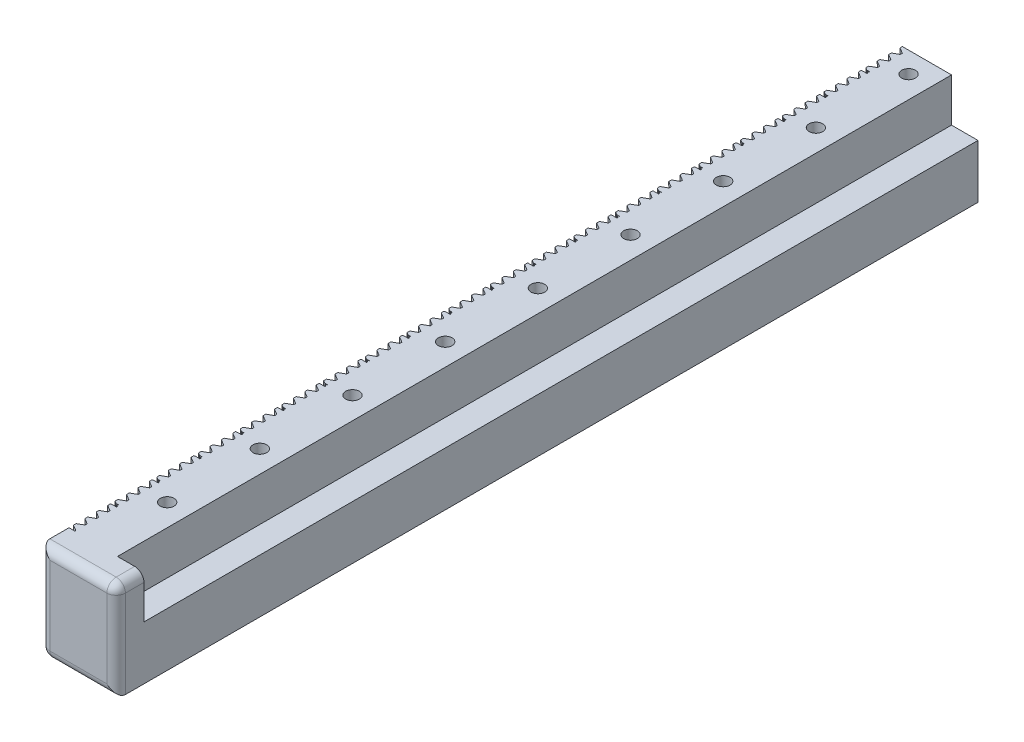
SolidWorks part; units mm, degrees
ref_plane "Front Plane" through (0, 0, 0) normal (0, 0, 1) x (1, 0, 0)
ref_plane "Top Plane" through (0, 0, 0) normal (0, 1, 0) x (1, 0, 0)
ref_plane "Right Plane" through (0, 0, 0) normal (1, 0, 0) x (0, 0, -1)
sketch "Sketch1" plane through (0, 0, 0) normal (0, 0, 1) x (1, 0, 0)
  line L0 (8.155, 3.5595) -> (8.155, -2.2289)
  line L1 (6.255, 0) -> (0.2882, 0)
  line L3 (0, 8.253) -> (5.3, 8.253)
  line L4 (5.3, 3.5595) -> (5.3, 8.253)
  line L5 (0.2882, 0) -> (0, 8.253)
  line L7 (5.3, 3.5595) -> (8.155, 3.5595)
  line L11 (8.155, -2.2289) -> (6.255, -2.2289)
  line L12 (6.255, 0) -> (6.255, -2.2289)
  dimension "D1" = 5.3
  dimension "D2" = 8.253
  dimension "D3" = 1.9
  dimension "D4" = 2.855
  dimension "D6" = 88
extrude "Boss-Extrude1" add sketch "Sketch1" along normal blind 90
sketch "Sketch2" plane through (0, 0, 90) normal (0, 0, 1) x (1, 0, 0)
  line L1 (0, 8.253) -> (8.155, 8.253)
  line L2 (0, 8.253) -> (0, -2.2289)
  line L3 (0, -2.2289) -> (8.155, -2.2289)
  line L4 (8.155, 8.253) -> (8.155, -2.2289)
extrude "Boss-Extrude2" add sketch "Sketch2" along normal blind 3
fillet "Fillet1" radius 1 6 edges at (4.0775, 8.253, 93) (8.155, 3.0121, 93) (4.0775, -2.2289, 93) (0, 3.0121, 93) (0, -2.2289, 91.5) (8.155, 8.253, 91.5)
sketch "Sketch3" plane through (5.3, 0, 0) normal (0, 1, 0) x (0, 0, -1)
  line L0 (-87.5812, 4.6774) -> (-88.0715, 5.5507)
  line L1 (-88.0715, 5.5507) -> (-88.5898, 4.6774)
  line L2 (-88.8112, 4.6774) -> (-89.3015, 5.5507)
  line L3 (-89.3015, 5.5507) -> (-89.8198, 4.6774)
  line L4 (-89.3983, 4.4813) -> (-88.7803, 4.4739) [skipped]
  line L5 (-86.3512, 4.6774) -> (-86.8415, 5.5507)
  line L6 (-86.8415, 5.5507) -> (-87.3598, 4.6774)
  line L7 (-85.1212, 4.6774) -> (-85.6115, 5.5507)
  line L8 (-85.6115, 5.5507) -> (-86.1298, 4.6774)
  line L149 (-89.9324, 4.6774) -> (-89.9324, 6.9221)
  line L150 (-89.9324, 6.9221) -> (-85.1212, 6.9221)
  line L154 (-89.8198, 4.6774) -> (-89.9324, 4.6774)
  line L155 (-88.5898, 4.6774) -> (-88.8112, 4.6774)
  line L156 (-87.3598, 4.6774) -> (-87.5812, 4.6774)
  line L157 (-86.1298, 4.6774) -> (-86.3512, 4.6774)
  line L158 (-85.1212, 6.9221) -> (-85.1212, 4.6774)
  line L160 (-83.1621, 7.6054) -> (-83.4775, 7.0739) [skipped]
  line L161 (-83.735, 6.5902) -> (-84.3402, 7.668) [skipped]
  line L162 (-81.9321, 7.6054) -> (-82.5629, 6.5424) [skipped]
  line L163 (-82.505, 6.5902) -> (-83.1102, 7.668) [skipped]
  line L164 (-80.7021, 7.6054) -> (-81.3329, 6.5424) [skipped]
  line L165 (-81.275, 6.5902) -> (-81.8802, 7.668) [skipped]
  line L166 (-79.4721, 7.6054) -> (-80.1029, 6.5424) [skipped]
  line L167 (-80.045, 6.5902) -> (-80.6502, 7.668) [skipped]
  line L168 (-78.2421, 7.6054) -> (-78.8729, 6.5424) [skipped]
  line L169 (-78.815, 6.5902) -> (-79.4202, 7.668) [skipped]
  line L170 (-77.0121, 7.6054) -> (-77.6429, 6.5424) [skipped]
  line L171 (-75.7821, 7.6054) -> (-76.4129, 6.5424) [skipped]
  line L172 (-84.965, 6.5902) -> (-85.5702, 7.668) [skipped]
  line L173 (-49.295, 6.5902) -> (-49.9002, 7.668) [skipped]
  line L174 (-47.4921, 7.6054) -> (-48.1229, 6.5424) [skipped]
  line L175 (-48.065, 6.5902) -> (-48.6702, 7.668) [skipped]
  line L176 (-46.2621, 7.6054) -> (-46.8929, 6.5424) [skipped]
  line L177 (-46.835, 6.5902) -> (-47.4402, 7.668) [skipped]
  line L178 (-45.0321, 7.6054) -> (-45.6629, 6.5424) [skipped]
  line L179 (-45.605, 6.5902) -> (-46.2102, 7.668) [skipped]
  line L180 (-43.8021, 7.6054) -> (-44.4329, 6.5424) [skipped]
  line L181 (-44.375, 6.5902) -> (-44.9802, 7.668) [skipped]
  line L182 (-42.5721, 7.6054) -> (-43.2029, 6.5424) [skipped]
  line L183 (-43.145, 6.5902) -> (-43.7502, 7.668) [skipped]
  line L184 (-41.3421, 7.6054) -> (-41.9729, 6.5424) [skipped]
  line L185 (-41.915, 6.5902) -> (-42.5202, 7.668) [skipped]
  line L186 (-40.1121, 7.6054) -> (-40.7429, 6.5424) [skipped]
  line L187 (-40.685, 6.5902) -> (-41.2902, 7.668) [skipped]
  line L188 (-38.8821, 7.6054) -> (-39.5129, 6.5424) [skipped]
  line L189 (-37.6521, 7.6054) -> (-38.2829, 6.5424) [skipped]
  line L190 (-38.225, 6.5902) -> (-38.8302, 7.668) [skipped]
  line L191 (-36.4221, 7.6054) -> (-37.0529, 6.5424) [skipped]
  line L192 (-36.995, 6.5902) -> (-37.6002, 7.668) [skipped]
  line L193 (-35.1921, 7.6054) -> (-35.8229, 6.5424) [skipped]
  line L194 (-35.765, 6.5902) -> (-36.3702, 7.668) [skipped]
  line L195 (-33.9621, 7.6054) -> (-34.5929, 6.5424) [skipped]
  line L196 (-34.535, 6.5902) -> (-35.1402, 7.668) [skipped]
  line L197 (-32.7321, 7.6054) -> (-33.3629, 6.5424) [skipped]
  line L198 (-33.305, 6.5902) -> (-33.9102, 7.668) [skipped]
  line L199 (-31.5021, 7.6054) -> (-32.1329, 6.5424) [skipped]
  line L200 (-32.075, 6.5902) -> (-32.6802, 7.668) [skipped]
  line L201 (-30.2721, 7.6054) -> (-30.9029, 6.5424) [skipped]
  line L202 (-30.845, 6.5902) -> (-31.4502, 7.668) [skipped]
  line L203 (-29.0421, 7.6054) -> (-29.6729, 6.5424) [skipped]
  line L204 (-29.615, 6.5902) -> (-30.2202, 7.668) [skipped]
  line L205 (-27.8121, 7.6054) -> (-28.4429, 6.5424) [skipped]
  line L206 (-28.385, 6.5902) -> (-28.9902, 7.668) [skipped]
  line L207 (-26.5821, 7.6054) -> (-27.2129, 6.5424) [skipped]
  line L208 (-27.155, 6.5902) -> (-27.7602, 7.668) [skipped]
  line L209 (-25.3521, 7.6054) -> (-25.9829, 6.5424) [skipped]
  line L210 (-25.925, 6.5902) -> (-26.5302, 7.668) [skipped]
  line L211 (-24.1221, 7.6054) -> (-24.7529, 6.5424) [skipped]
  line L212 (-24.695, 6.5902) -> (-25.3002, 7.668) [skipped]
  line L213 (-22.8921, 7.6054) -> (-23.5229, 6.5424) [skipped]
  line L214 (-23.465, 6.5902) -> (-24.0702, 7.668) [skipped]
  line L215 (-21.6621, 7.6054) -> (-22.2929, 6.5424) [skipped]
  line L216 (-22.235, 6.5902) -> (-22.8402, 7.668) [skipped]
  line L217 (-20.4321, 7.6054) -> (-21.0629, 6.5424) [skipped]
  line L218 (-21.005, 6.5902) -> (-21.6102, 7.668) [skipped]
  line L219 (-19.2021, 7.6054) -> (-19.8329, 6.5424) [skipped]
  line L220 (-19.775, 6.5902) -> (-20.3802, 7.668) [skipped]
  line L221 (-17.9721, 7.6054) -> (-18.6029, 6.5424) [skipped]
  line L222 (-18.545, 6.5902) -> (-19.1502, 7.668) [skipped]
  line L223 (-16.7421, 7.6054) -> (-17.3729, 6.5424) [skipped]
  line L224 (-17.315, 6.5902) -> (-17.9202, 7.668) [skipped]
  line L225 (-15.5121, 7.6054) -> (-16.1429, 6.5424) [skipped]
  line L226 (-16.085, 6.5902) -> (-16.6902, 7.668) [skipped]
  line L227 (-14.2821, 7.6054) -> (-14.9129, 6.5424) [skipped]
  line L228 (-14.855, 6.5902) -> (-15.4602, 7.668) [skipped]
  line L229 (-13.0521, 7.6054) -> (-13.6829, 6.5424) [skipped]
  line L230 (-13.625, 6.5902) -> (-14.2302, 7.668) [skipped]
  line L231 (-11.8221, 7.6054) -> (-12.4529, 6.5424) [skipped]
  line L232 (-12.395, 6.5902) -> (-13.0002, 7.668) [skipped]
  line L233 (-10.5921, 7.6054) -> (-11.2229, 6.5424) [skipped]
  line L234 (-11.165, 6.5902) -> (-11.7702, 7.668) [skipped]
  line L235 (-9.3621, 7.6054) -> (-9.9929, 6.5424) [skipped]
  line L236 (-9.935, 6.5902) -> (-10.5402, 7.668) [skipped]
  line L237 (-8.1321, 7.6054) -> (-8.7629, 6.5424) [skipped]
  line L238 (-8.705, 6.5902) -> (-9.3102, 7.668) [skipped]
  line L239 (-6.9021, 7.6054) -> (-7.5329, 6.5424) [skipped]
  line L240 (-7.475, 6.5902) -> (-8.0802, 7.668) [skipped]
  line L241 (-5.6721, 7.6054) -> (-6.3029, 6.5424) [skipped]
  line L242 (-6.245, 6.5902) -> (-6.8502, 7.668) [skipped]
  line L243 (-4.4421, 7.6054) -> (-5.0729, 6.5424) [skipped]
  line L244 (-5.015, 6.5902) -> (-5.6202, 7.668) [skipped]
  line L245 (-3.2121, 7.6054) -> (-3.8429, 6.5424) [skipped]
  line L246 (-3.785, 6.5902) -> (-4.3902, 7.668) [skipped]
  line L247 (-1.9821, 7.6054) -> (-2.6129, 6.5424) [skipped]
  line L248 (-2.555, 6.5902) -> (-3.1602, 7.668) [skipped]
  line L249 (-0.7521, 7.6054) -> (-1.3829, 6.5424) [skipped]
  line L250 (-1.325, 6.5902) -> (-1.9302, 7.668) [skipped]
  line L251 (0.4779, 7.6054) -> (-0.1529, 6.5424) [skipped]
  line L252 (-0.095, 6.5902) -> (-0.7002, 7.668) [skipped]
  line L253 (1.7079, 7.6054) -> (1.0771, 6.5424) [skipped]
  line L254 (-39.455, 6.5902) -> (-40.0602, 7.668) [skipped]
  line L255 (-76.355, 6.5902) -> (-76.9602, 7.668) [skipped]
  line L256 (-74.5521, 7.6054) -> (-75.1829, 6.5424) [skipped]
  line L257 (-75.125, 6.5902) -> (-75.7302, 7.668) [skipped]
  line L258 (-73.3221, 7.6054) -> (-73.9529, 6.5424) [skipped]
  line L259 (-73.895, 6.5902) -> (-74.5002, 7.668) [skipped]
  line L260 (-72.0921, 7.6054) -> (-72.7229, 6.5424) [skipped]
  line L261 (-72.665, 6.5902) -> (-73.2702, 7.668) [skipped]
  line L262 (-70.8621, 7.6054) -> (-71.4929, 6.5424) [skipped]
  line L263 (-71.435, 6.5902) -> (-72.0402, 7.668) [skipped]
  line L264 (-69.6321, 7.6054) -> (-70.2629, 6.5424) [skipped]
  line L265 (-70.205, 6.5902) -> (-70.8102, 7.668) [skipped]
  line L266 (-68.4021, 7.6054) -> (-69.0329, 6.5424) [skipped]
  line L267 (-68.975, 6.5902) -> (-69.5802, 7.668) [skipped]
  line L268 (-67.1721, 7.6054) -> (-67.8029, 6.5424) [skipped]
  line L269 (-67.745, 6.5902) -> (-68.3502, 7.668) [skipped]
  line L270 (-65.9421, 7.6054) -> (-66.5729, 6.5424) [skipped]
  line L271 (-66.515, 6.5902) -> (-67.1202, 7.668) [skipped]
  line L272 (-64.7121, 7.6054) -> (-65.3429, 6.5424) [skipped]
  line L273 (-65.285, 6.5902) -> (-65.8902, 7.668) [skipped]
  line L274 (-63.4821, 7.6054) -> (-64.1129, 6.5424) [skipped]
  line L275 (-64.055, 6.5902) -> (-64.6602, 7.668) [skipped]
  line L276 (-62.2521, 7.6054) -> (-62.8829, 6.5424) [skipped]
  line L277 (-62.825, 6.5902) -> (-63.4302, 7.668) [skipped]
  line L278 (-61.0221, 7.6054) -> (-61.6529, 6.5424) [skipped]
  line L279 (-61.595, 6.5902) -> (-62.2002, 7.668) [skipped]
  line L280 (-59.7921, 7.6054) -> (-60.4229, 6.5424) [skipped]
  line L281 (-60.365, 6.5902) -> (-60.9702, 7.668) [skipped]
  line L282 (-58.5621, 7.6054) -> (-59.1929, 6.5424) [skipped]
  line L283 (-59.135, 6.5902) -> (-59.7402, 7.668) [skipped]
  line L284 (-57.3321, 7.6054) -> (-57.9629, 6.5424) [skipped]
  line L285 (-57.905, 6.5902) -> (-58.5102, 7.668) [skipped]
  line L286 (-56.1021, 7.6054) -> (-56.7329, 6.5424) [skipped]
  line L287 (-56.675, 6.5902) -> (-57.2802, 7.668) [skipped]
  line L288 (-54.8721, 7.6054) -> (-55.5029, 6.5424) [skipped]
  line L289 (-55.445, 6.5902) -> (-56.0502, 7.668) [skipped]
  line L290 (-53.6421, 7.6054) -> (-54.2729, 6.5424) [skipped]
  line L291 (-54.215, 6.5902) -> (-54.8202, 7.668) [skipped]
  line L292 (-52.4121, 7.6054) -> (-53.0429, 6.5424) [skipped]
  line L293 (-52.985, 6.5902) -> (-53.5902, 7.668) [skipped]
  line L294 (-51.1821, 7.6054) -> (-51.8129, 6.5424) [skipped]
  line L295 (-51.755, 6.5902) -> (-52.3602, 7.668) [skipped]
  line L296 (-49.9521, 7.6054) -> (-50.5829, 6.5424) [skipped]
  line L297 (-50.525, 6.5902) -> (-51.1302, 7.668) [skipped]
  line L298 (-48.7221, 7.6054) -> (-49.3529, 6.5424) [skipped]
  line L299 (-77.585, 6.5902) -> (-78.1902, 7.668) [skipped]
  circle A0 centre (-89.3101, 4.8371) radius 0.3568 construction
  arc A1 (-87.7689, 5.0118) -> (-88.3869, 5.0193) centre (-88.0801, 4.8371) ccw construction
  arc A2 (-86.5389, 5.0118) -> (-87.1692, 4.6774) centre (-86.8501, 4.8371) ccw construction
  arc A3 (-85.9392, 4.6774) -> (-85.301, 4.6774) centre (-85.6201, 4.8371) ccw construction
  arc A74 (-85.3089, 5.0118) -> (-85.9269, 5.0193) centre (-85.6201, 4.8371) ccw construction
  arc A75 (-84.7112, 4.6816) -> (-84.7116, 4.6824) centre (-84.3901, 4.8371) ccw construction
  circle A76 centre (-83.1601, 4.8371) radius 0.3568 construction
  circle A77 centre (-81.9301, 4.8371) radius 0.3568 construction
  circle A78 centre (-80.7001, 4.8371) radius 0.3568 construction
  circle A79 centre (-79.4701, 4.8371) radius 0.3568 construction
  circle A80 centre (-78.2401, 4.8371) radius 0.3568 construction
  circle A81 centre (-77.0101, 4.8371) radius 0.3568 construction
  circle A82 centre (-48.7201, 4.8371) radius 0.3568 construction
  circle A83 centre (-47.4901, 4.8371) radius 0.3568 construction
  circle A84 centre (-46.2601, 4.8371) radius 0.3568 construction
  circle A85 centre (-45.0301, 4.8371) radius 0.3568 construction
  circle A86 centre (-43.8001, 4.8371) radius 0.3568 construction
  circle A87 centre (-42.5701, 4.8371) radius 0.3568 construction
  circle A88 centre (-41.3401, 4.8371) radius 0.3568 construction
  circle A89 centre (-40.1101, 4.8371) radius 0.3568 construction
  circle A90 centre (-38.8801, 4.8371) radius 0.3568 construction
  circle A91 centre (-37.6501, 4.8371) radius 0.3568 construction
  circle A92 centre (-36.4201, 4.8371) radius 0.3568 construction
  circle A93 centre (-35.1901, 4.8371) radius 0.3568 construction
  circle A94 centre (-33.9601, 4.8371) radius 0.3568 construction
  circle A95 centre (-32.7301, 4.8371) radius 0.3568 construction
  circle A96 centre (-31.5001, 4.8371) radius 0.3568 construction
  circle A97 centre (-30.2701, 4.8371) radius 0.3568 construction
  circle A98 centre (-29.0401, 4.8371) radius 0.3568 construction
  circle A99 centre (-27.8101, 4.8371) radius 0.3568 construction
  circle A100 centre (-26.5801, 4.8371) radius 0.3568 construction
  circle A101 centre (-25.3501, 4.8371) radius 0.3568 construction
  circle A102 centre (-24.1201, 4.8371) radius 0.3568 construction
  circle A103 centre (-22.8901, 4.8371) radius 0.3568 construction
  circle A104 centre (-21.6601, 4.8371) radius 0.3568 construction
  circle A105 centre (-20.4301, 4.8371) radius 0.3568 construction
  circle A106 centre (-19.2001, 4.8371) radius 0.3568 construction
  circle A107 centre (-17.9701, 4.8371) radius 0.3568 construction
  circle A108 centre (-16.7401, 4.8371) radius 0.3568 construction
  circle A109 centre (-15.5101, 4.8371) radius 0.3568 construction
  circle A110 centre (-14.2801, 4.8371) radius 0.3568 construction
  circle A111 centre (-13.0501, 4.8371) radius 0.3568 construction
  circle A112 centre (-11.8201, 4.8371) radius 0.3568 construction
  circle A113 centre (-10.5901, 4.8371) radius 0.3568 construction
  circle A114 centre (-9.3601, 4.8371) radius 0.3568 construction
  circle A115 centre (-8.1301, 4.8371) radius 0.3568 construction
  circle A116 centre (-6.9001, 4.8371) radius 0.3568 construction
  circle A117 centre (-5.6701, 4.8371) radius 0.3568 construction
  circle A118 centre (-4.4401, 4.8371) radius 0.3568 construction
  circle A119 centre (-3.2101, 4.8371) radius 0.3568 construction
  circle A120 centre (-1.9801, 4.8371) radius 0.3568 construction
  circle A121 centre (-0.7501, 4.8371) radius 0.3568 construction
  circle A122 centre (0.4799, 4.8371) radius 0.3568 construction
  circle A123 centre (-75.7801, 4.8371) radius 0.3568 construction
  circle A124 centre (-74.5501, 4.8371) radius 0.3568 construction
  circle A125 centre (-73.3201, 4.8371) radius 0.3568 construction
  circle A126 centre (-72.0901, 4.8371) radius 0.3568 construction
  circle A127 centre (-70.8601, 4.8371) radius 0.3568 construction
  circle A128 centre (-69.6301, 4.8371) radius 0.3568 construction
  circle A129 centre (-68.4001, 4.8371) radius 0.3568 construction
  circle A130 centre (-67.1701, 4.8371) radius 0.3568 construction
  circle A131 centre (-65.9401, 4.8371) radius 0.3568 construction
  circle A132 centre (-64.7101, 4.8371) radius 0.3568 construction
  circle A133 centre (-63.4801, 4.8371) radius 0.3568 construction
  circle A134 centre (-62.2501, 4.8371) radius 0.3568 construction
  circle A135 centre (-61.0201, 4.8371) radius 0.3568 construction
  circle A136 centre (-59.7901, 4.8371) radius 0.3568 construction
  circle A137 centre (-58.5601, 4.8371) radius 0.3568 construction
  circle A138 centre (-57.3301, 4.8371) radius 0.3568 construction
  circle A139 centre (-56.1001, 4.8371) radius 0.3568 construction
  circle A140 centre (-54.8701, 4.8371) radius 0.3568 construction
  circle A141 centre (-53.6401, 4.8371) radius 0.3568 construction
  circle A142 centre (-52.4101, 4.8371) radius 0.3568 construction
  circle A143 centre (-51.1801, 4.8371) radius 0.3568 construction
  circle A144 centre (-49.9501, 4.8371) radius 0.3568 construction
  dimension "D2" = 74
extrude "Cut-Extrude2" cut sketch "Sketch3" along normal blind 13
pattern_linear "LPattern1" count 20 spacing 4.5 along (0, 0, -1) of "Cut-Extrude2"
sketch "Sketch4" plane through (0, 8.253, 0) normal (0, 1, 0) x (1, 0, 0)
  circle A0 centre (2.9148, -2.2514) radius 0.7382
  circle A1 centre (2.9148, -12.2514) radius 0.7382
  circle A2 centre (2.9148, -22.2514) radius 0.7382
  circle A3 centre (2.9148, -32.2514) radius 0.7382
  circle A4 centre (2.9148, -42.2514) radius 0.7382
  circle A5 centre (2.9148, -52.2514) radius 0.7382
  circle A6 centre (2.9148, -62.2514) radius 0.7382
  circle A7 centre (2.9148, -72.2514) radius 0.7382
  circle A8 centre (2.9148, -82.2514) radius 0.7382
  dimension "D1" = 9
extrude "Cut-Extrude3" cut sketch "Sketch4" against normal blind 18
